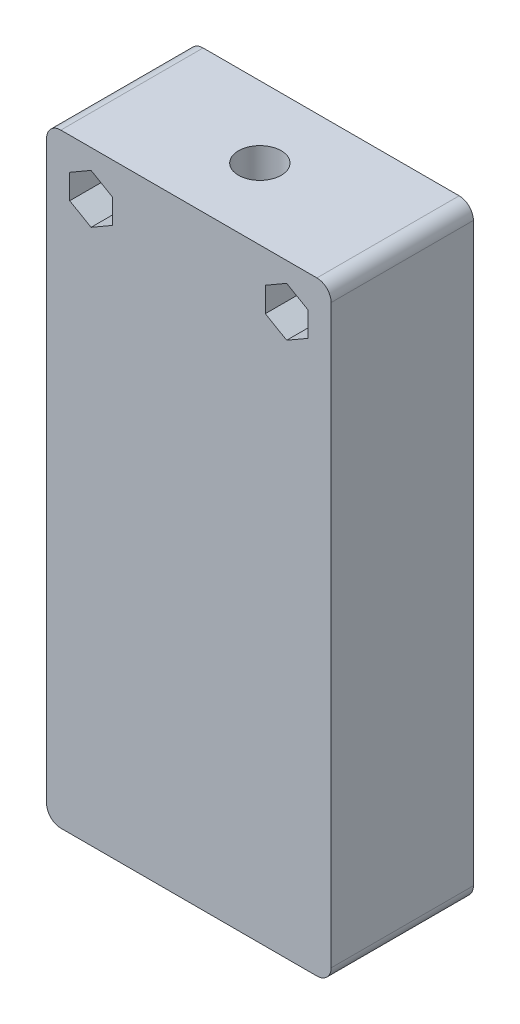
SolidWorks part; units mm, degrees
ref_plane "Front Plane" through (0, 0, 0) normal (0, 0, 1) x (1, 0, 0)
ref_plane "Top Plane" through (0, 0, 0) normal (0, 1, 0) x (1, 0, 0)
ref_plane "Right Plane" through (0, 0, 0) normal (1, 0, 0) x (0, 0, -1)
sketch "Эскиз1" plane through (0, 0, 0) normal (0, 0, 1) x (1, 0, 0)
  line L1 (0, 0) -> (-40, 0)
  line L2 (0, 0) -> (0, -85)
  line L3 (0, -85) -> (-40, -85)
  line L4 (-40, 0) -> (-40, -85)
  dimension "D1" = 40
  dimension "D2" = 85
extrude "Бобышка-Вытянуть1" add sketch "Эскиз1" along normal blind 20
sketch "Эскиз2" plane through (0, 0, 0) normal (0, 0, -1) x (-1, 0, 0)
  line L0 (20, -6) -> (20, 0) construction
  line L1 (5, -6) -> (35, -6)
  line L2 (5, -6) -> (5, -66)
  line L3 (5, -66) -> (35, -66)
  line L4 (35, -6) -> (35, -66)
  line L5 (0, 0) -> (40, 0) construction
  dimension "D1" = 30
  dimension "D2" = 60
  dimension "D3" = 6
extrude "Вырез-Вытянуть1" cut sketch "Эскиз2" against normal blind 15
sketch "Эскиз3" plane through (0, -85, 0) normal (0, -1, 0) x (1, 0, 0)
  line L0 (-20, 8) -> (-20, 20) construction
  line L1 (-35.75, 16) -> (-4.25, 16)
  line L2 (-35.75, 16) -> (-35.75, 0)
  line L3 (-35.75, 0) -> (-4.25, 0)
  line L4 (-4.25, 16) -> (-4.25, 0)
  line L5 (-35.75, 16) -> (-4.25, 0) construction
  line L6 (-35.75, 0) -> (-4.25, 16) construction
  line L7 (-40, 20) -> (0, 20) construction
  line L8 (-40, 0) -> (0, 0) construction
  point P0 (-20, 8)
  dimension "D1" = 16
  dimension "D2" = 31.5
extrude "Вырез-Вытянуть3" cut sketch "Эскиз3" against normal blind 7
sketch "Эскиз4" plane through (0, -78, 0) normal (0, -1, 0) x (1, 0, 0)
  line L0 (-7.5, 9.6362) -> (-32.5, 9.6362) construction
  line L1 (-20, 9.6362) -> (-20, 16) construction
  line L2 (-4.25, 16) -> (-35.75, 16) construction
  line L8 (-35.75, 0) -> (-4.25, 0) construction
  circle A0 centre (-7.5, 9.6362) radius 1.5
  circle A1 centre (-32.5, 9.6362) radius 1.5
  point P8 (-10.1832, 9.6362)
  point P9 (-20, 15.3)
  line B0 (-13.5314, 15.3) -> (-26.4686, 15.3)
  line B1 (-29.2261, 12.9862) -> (-30.4075, 6.2862)
  line B2 (-27.65, 3) -> (-12.35, 3)
  line B3 (-9.5925, 6.2862) -> (-10.7739, 12.9862)
  arc B4 (-10.7739, 12.9862) -> (-13.5314, 15.3) centre (-13.5314, 12.5) ccw
  arc B5 (-26.4686, 15.3) -> (-29.2261, 12.9862) centre (-26.4686, 12.5) ccw
  arc B6 (-30.4075, 6.2862) -> (-27.65, 3) centre (-27.65, 5.8) ccw
  arc B7 (-12.35, 3) -> (-9.5925, 6.2862) centre (-12.35, 5.8) ccw
  dimension "D1" = 3
  dimension "D2" = 3
  dimension "D3" = 25
  dimension "D4" = 3
sketch_block_instance "Блок1-1"
sketch_block "Блок1"
extrude "Вырез-Вытянуть4" cut sketch "Эскиз4" against normal blind 16
fillet "Скругление1" radius 2 2 edges at (-4.25, -81.5, 16) (-35.75, -81.5, 16)
fillet "Скругление2" radius 2 4 edges at (-40, -85, 10) (0, -85, 10) (-40, 0, 10) (0, 0, 10)
sketch "Эскиз6" plane through (0, 0, 0) normal (0, 0, -1) x (-1, 0, 0)
  line L0 (5, -66) -> (35, -66) construction
  line L1 (12.35, -66) -> (27.65, -66)
  line L2 (12.35, -66) -> (12.35, -78)
  line L3 (12.35, -78) -> (27.65, -78)
  line L4 (27.65, -66) -> (27.65, -78)
  line L5 (35.75, -78) -> (4.25, -78) construction
  line L6 (20, -66) -> (20, -6) construction
  line L7 (35, -6) -> (5, -6) construction
extrude "Вырез-Вытянуть5" cut sketch "Эскиз6" against normal blind 4
sketch "Эскиз7" plane through (0, 0, 15) normal (0, 0, -1) x (-1, 0, 0)
  line L0 (35, -6) -> (5, -6) construction
  line L2 (11.6, -6) -> (11.6, -58)
  line L3 (11.6, -58) -> (25.6, -58) construction
  line L4 (25.6, -6) -> (25.6, -58)
  line L5 (18.6, -58) -> (18.6, -40.268) construction
  line L6 (25.6, -58) -> (28.6, -58)
  line L7 (28.6, -58) -> (28.6, -6)
  line L8 (35, -6) -> (5, -6) construction
  line L9 (6.25, -85) -> (33.75, -85) construction
  line L10 (28.6, -6) -> (25.6, -6)
  line L11 (11.6, -58) -> (8.6, -58)
  line L12 (8.6, -58) -> (8.6, -6)
  line L13 (8.6, -6) -> (11.6, -6)
  point P10 (20, -85)
  dimension "D1" = 1.4
  dimension "D2" = 14
  dimension "D3" = 52
  dimension "D4" = 3
extrude "Бобышка-Вытянуть2" add sketch "Эскиз7" along normal blind 10
sketch "Эскиз8" plane through (0, -6, 0) normal (0, -1, 0) x (1, 0, 0)
  line L0 (-11.6, 5) -> (-8.6, 5) construction
  line L1 (-10.1, 5) -> (-27.1, 5)
  line L2 (-10.1, 5) -> (-10.1, 3.5)
  line L3 (-10.1, 3.5) -> (-27.1, 3.5)
  line L4 (-27.1, 5) -> (-27.1, 3.5)
  line L5 (-28.6, 5) -> (-25.6, 5) construction
  dimension "D1" = 1.5
extrude "Вырез-Вытянуть6" cut sketch "Эскиз8" against normal blind 2
chamfer "Фаска1" distance 0.7 angle 45 1 edges at (-18.6, -4, 3.5)
sketch "Эскиз9" plane through (0, -6, 0) normal (0, -1, 0) x (1, 0, 0)
  line L0 (-20, 10.0228) -> (-20, 0) construction
  line L1 (-35, 0) -> (-5, 0) construction
  circle A0 centre (-20, 10.0228) radius 3
  dimension "D1" = 6
extrude "Вырез-Вытянуть7" cut sketch "Эскиз9" against normal blind 15
sketch "Эскиз10" plane through (0, -66, 0) normal (0, 1, 0) x (1, 0, 0)
  line L0 (-35, -15) -> (-35, 0) construction
  line L1 (-35, -2) -> (-32, -2)
  line L2 (-35, -2) -> (-35, -5)
  line L3 (-35, -5) -> (-32, -5)
  line L4 (-32, -2) -> (-32, -5)
  line L5 (-5, -15) -> (-5, 0) construction
  line L6 (-5, -2) -> (-8, -2)
  line L7 (-5, -2) -> (-5, -5)
  line L8 (-5, -5) -> (-8, -5)
  line L9 (-8, -2) -> (-8, -5)
  line L10 (-8, -2) -> (-32, -2) construction
  line L12 (-27.65, 0) -> (-35, 0) construction
  dimension "D1" = 3
  dimension "D2" = 3
  dimension "D3" = 2
extrude "Вырез-Вытянуть8" cut sketch "Эскиз10" against normal blind 2.5
sketch "Эскиз11" plane through (0, 0, 0) normal (0, 1, 0) x (1, 0, 0)
  line L0 (-31.8, -10.0228) -> (-20, -10.0228) construction
  line L2 (-31.8, -10.0228) -> (-31.8, -15) construction
  line L3 (-35, -15) -> (-28.6, -15) construction
  circle A0 centre (-31.8, -10.0228) radius 2.5
  point P8 (-31.8, -15)
  dimension "D1" = 5
extrude "Вырез-Вытянуть9" [suppressed] cut sketch "Эскиз11" against normal blind 11.5
sketch "Эскиз14" plane through (0, 0, 0) normal (0, 0, -1) x (-1, 0, 0)
  line L0 (2, 0) -> (38, 0) construction
  line L1 (40, -2) -> (40, -83) construction
  line L2 (0, -83) -> (0, -2) construction
  circle A0 centre (6.25, -6.25) radius 6.25
  circle A1 centre (33.75, -6.25) radius 6.25
  dimension "D1" = 12.5
extrude "Бобышка-Вытянуть4" add sketch "Эскиз14" along normal up to surface (10 mm away) from surface at -15 up to face at (-18.6, -23, 5) starting at face at (-19.3, -41, 15)
sketch "Эскиз16" plane through (0, 0, 0) normal (0, 0, -1) x (-1, 0, 0)
  circle A0 centre (6.25, -6.25) radius 5
  circle A1 centre (33.75, -6.25) radius 5
  arc A2 (11.6, -9.4811) -> (12.495, -6) centre (6.25, -6.25) ccw construction
  arc A3 (28.6, -9.7912) -> (35, -12.3737) centre (33.75, -6.25) ccw construction
  dimension "D1" = 10
  dimension "D2" = 10
extrude "Вырез-Вытянуть10" cut sketch "Эскиз16" against normal up to surface (5 mm away)
sketch "Эскиз17" plane through (0, 0, 5) normal (0, 0, -1) x (-1, 0, 0)
  circle A0 centre (6.25, -6.25) radius 1.8
  circle A1 centre (33.75, -6.25) radius 1.8
  arc A2 (35, -11.0912) -> (28.7563, -6) centre (33.75, -6.25) ccw construction
  arc A3 (11.2437, -6) -> (5, -11.0912) centre (6.25, -6.25) ccw construction
  dimension "D1" = 3.6
  dimension "D2" = 3.6
extrude "Вырез-Вытянуть11" cut sketch "Эскиз17" against normal through all
sketch "Эскиз18" plane through (0, 0, 20) normal (0, 0, 1) x (1, 0, 0)
  line L1 (-6.25, -9.7141) -> (-3.25, -7.9821)
  line L2 (-3.25, -7.9821) -> (-3.25, -4.5179)
  line L3 (-3.25, -4.5179) -> (-6.25, -2.7859)
  line L4 (-6.25, -2.7859) -> (-9.25, -4.5179)
  line L5 (-9.25, -4.5179) -> (-9.25, -7.9821)
  line L6 (-9.25, -7.9821) -> (-6.25, -9.7141)
  line L7 (-30.75, -4.5179) -> (-33.75, -2.7859)
  line L8 (-33.75, -2.7859) -> (-36.75, -4.5179)
  line L9 (-36.75, -4.5179) -> (-36.75, -7.9821)
  line L10 (-36.75, -7.9821) -> (-33.75, -9.7141)
  line L11 (-33.75, -9.7141) -> (-30.75, -7.9821)
  line L12 (-30.75, -7.9821) -> (-30.75, -4.5179)
  circle A0 centre (-6.25, -6.25) radius 3 construction
  circle A1 centre (-33.75, -6.25) radius 3 construction
  dimension "D1" = 6
  dimension "D2" = 6
extrude "Вырез-Вытянуть12" cut sketch "Эскиз18" against normal offset from surface (12 mm away) 3 up to face at (-8.05, -6.25, 5)
